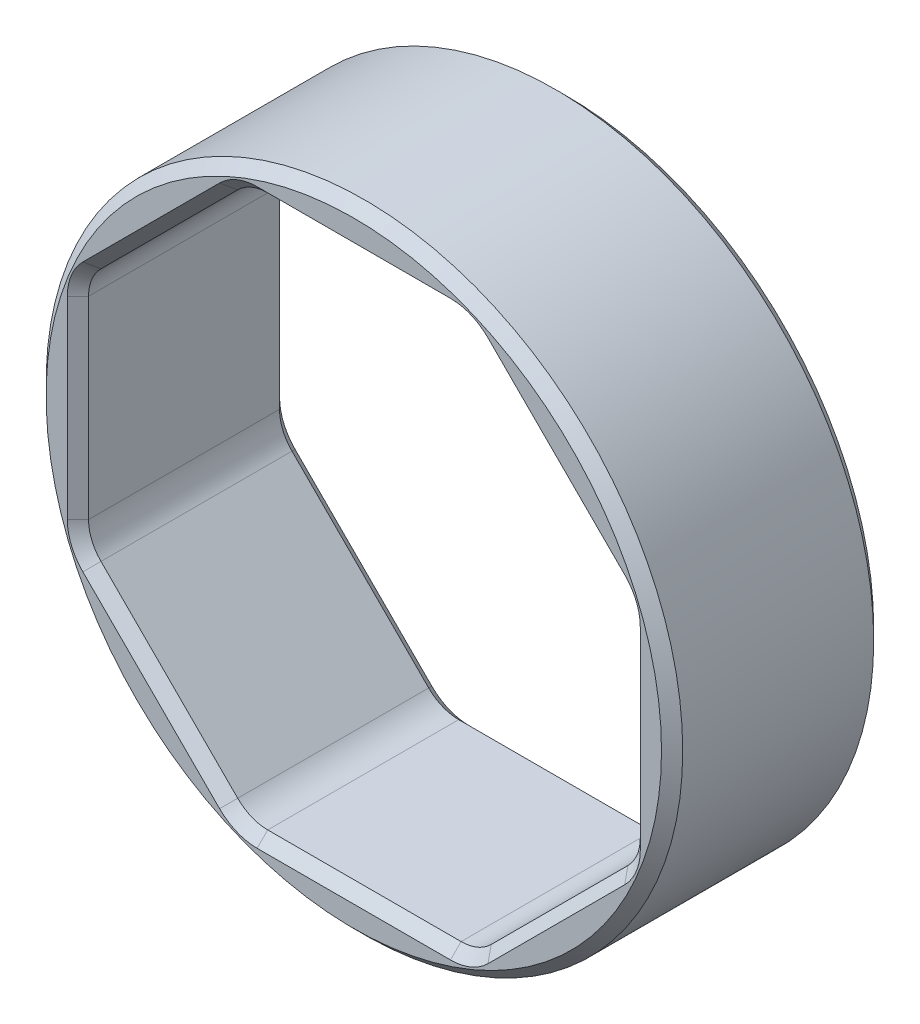
SolidWorks part; units mm, degrees
material "1060 Alloy"
ref_plane "Front Plane" through (0, 0, 0) normal (0, 0, 1) x (1, 0, 0)
ref_plane "Top Plane" through (0, 0, 0) normal (0, 1, 0) x (1, 0, 0)
ref_plane "Right Plane" through (0, 0, 0) normal (1, 0, 0) x (0, 0, -1)
sketch "Sketch1" plane through (0, 0, 0) normal (0, 0, 1) x (1, 0, 0)
  line L1 (-6.5, 2.6924) -> (-6.5, -2.6924)
  line L2 (-6.5, -2.6924) -> (-2.6924, -6.5)
  line L3 (-2.6924, -6.5) -> (2.6924, -6.5)
  line L4 (2.6924, -6.5) -> (6.5, -2.6924)
  line L5 (6.5, -2.6924) -> (6.5, 2.6924)
  line L6 (6.5, 2.6924) -> (2.6924, 6.5)
  line L7 (2.6924, 6.5) -> (-2.6924, 6.5)
  line L8 (-2.6924, 6.5) -> (-6.5, 2.6924)
  circle A0 centre (0, 0) radius 7.5
  circle A1 centre (0, 0) radius 7.5 construction
  circle A2 centre (0, 0) radius 6.5 construction
  dimension "D1" = 13
extrude "Boss-Extrude1" add sketch "Sketch1" along normal mid plane 5
fillet "Fillet1" radius 1
chamfer "Chamfer1" distance 0.25 angle 45
